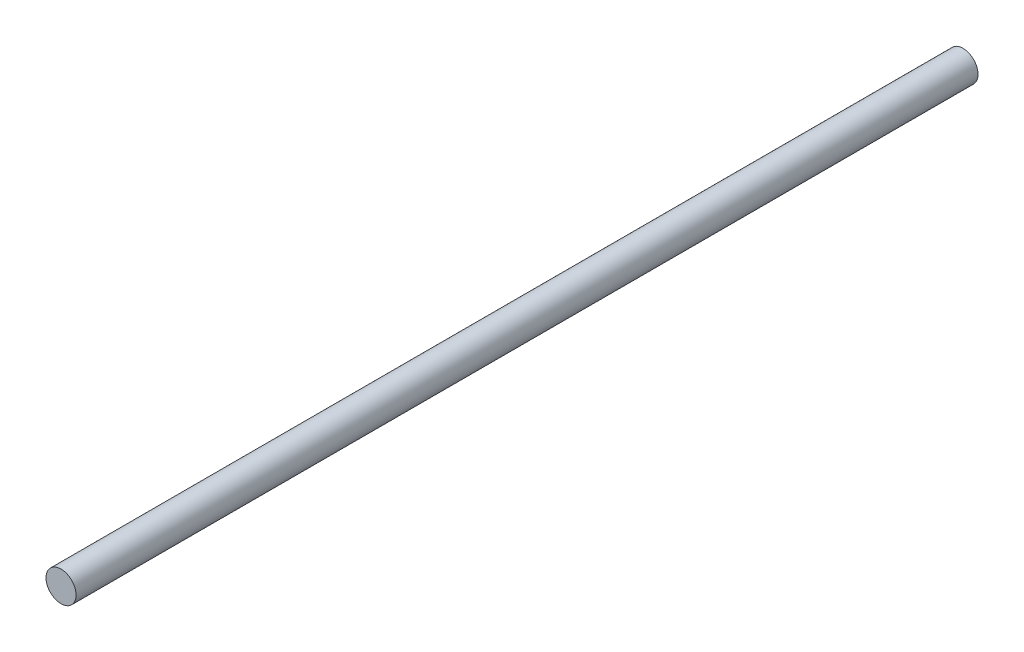
SolidWorks part; units mm, degrees
material "Balsa"
ref_plane "Alzado" through (0, 0, 0) normal (0, 0, 1) x (1, 0, 0)
ref_plane "Planta" through (0, 0, 0) normal (0, 1, 0) x (1, 0, 0)
ref_plane "Vista lateral" through (0, 0, 0) normal (1, 0, 0) x (0, 0, -1)
sketch "Croquis1" plane through (0, 0, 0) normal (0, 0, 1) x (1, 0, 0)
  circle A0 centre (0, 0) radius 1.5
  dimension "D1" = 3
extrude "Saliente-Extruir1" add sketch "Croquis1" along normal blind 90
